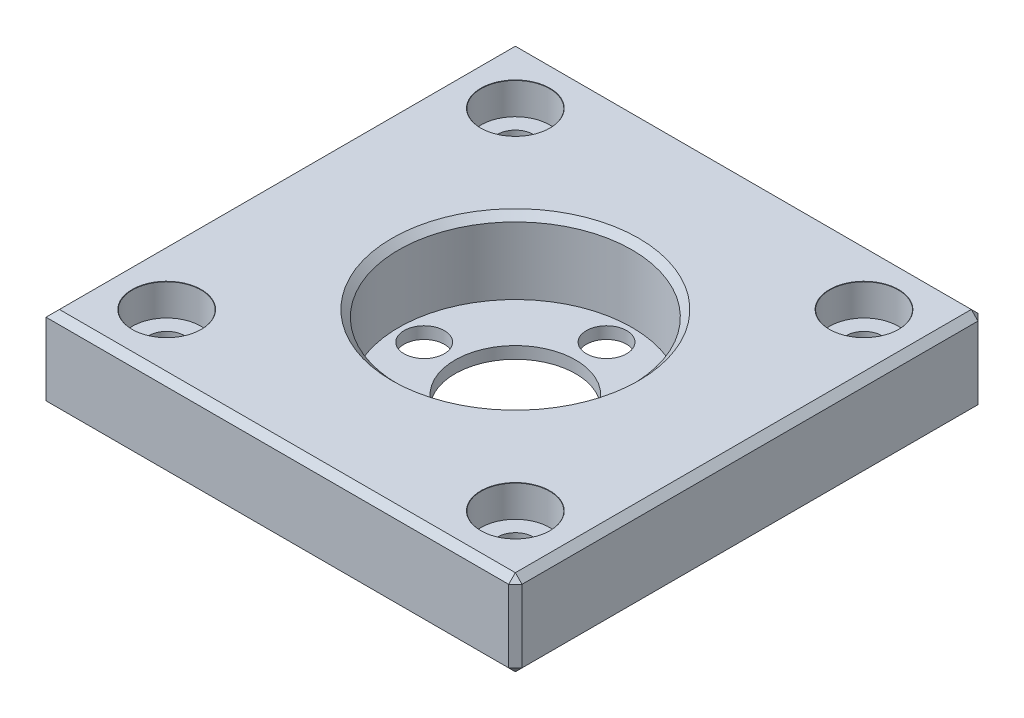
SolidWorks part; units mm, degrees
ref_plane "Front Plane" through (0, 0, 0) normal (0, 0, 1) x (1, 0, 0)
ref_plane "Top Plane" through (0, 0, 0) normal (0, 1, 0) x (1, 0, 0)
ref_plane "Right Plane" through (0, 0, 0) normal (1, 0, 0) x (0, 0, -1)
sketch "Sketch1" plane through (0, 0, 0) normal (0, 1, 0) x (1, 0, 0)
  line L1 (0, 0) -> (44.45, 0)
  line L2 (0, 0) -> (0, 44.45)
  line L3 (0, 44.45) -> (44.45, 44.45)
  line L4 (44.45, 0) -> (44.45, 44.45)
  dimension "D1" = 44.45
extrude "Boss-Extrude1" add sketch "Sketch1" along normal blind 8.128
sketch "Sketch2" plane through (0, 8.128, 0) normal (0, 1, 0) x (1, 0, 0)
  line L0 (22.225, 44.45) -> (22.225, 0) construction
  line L1 (44.45, 44.45) -> (0, 44.45) construction
  line L2 (0, 0) -> (44.45, 0) construction
  circle A0 centre (22.225, 22.225) radius 11.05
  point P4 (22.225, 26.2344)
  dimension "D1" = 22.1
extrude "Cut-Extrude1" cut sketch "Sketch2" against normal blind 7
sketch "Sketch3" plane through (0, 1.128, 0) normal (0, 1, 0) x (1, 0, 0)
  line L0 (22.225, 22.225) -> (22.225, 33.275) construction
  circle A0 centre (22.225, 30.861) radius 1.905
  circle A2 centre (22.225, 22.225) radius 11.05 construction
  circle A3 centre (30.861, 22.225) radius 1.905
  circle A4 centre (22.225, 13.589) radius 1.905
  circle A5 centre (13.589, 22.225) radius 1.905
  circle A6 centre (22.225, 22.225) radius 5.715
  point P5 (22.225, 22.225)
  point P16 (22.225, 22.225)
  dimension "D1" = 3.81
  dimension "D2" = 8.636
  dimension "D4" = 11.43
  dimension "D3" = 4
extrude "Cut-Extrude2" cut sketch "Sketch3" against normal through all
sketch "Sketch4" plane through (0, 8.128, 0) normal (0, 1, 0) x (1, 0, 0)
  line L0 (44.45, 44.45) -> (0, 44.45) construction
  line L1 (0, 44.45) -> (44.45, 44.45)
  line L2 (0, 44.45) -> (0, 0)
  line L3 (0, 0) -> (44.45, 0)
  line L4 (44.45, 44.45) -> (44.45, 0)
  line L5 (0, 44.45) -> (0, 0) construction
  line L6 (22.225, 44.45) -> (22.225, 0) construction
  line L7 (38.735, 5.715) -> (5.715, 5.715)
  line L8 (38.735, 5.715) -> (38.735, 38.735)
  line L9 (38.735, 38.735) -> (5.715, 38.735)
  line L10 (5.715, 5.715) -> (5.715, 38.735)
  line L11 (38.735, 5.715) -> (5.715, 38.735) construction
  line L12 (38.735, 38.735) -> (5.715, 5.715) construction
  point P9 (22.225, 22.225)
  point P14 (22.5364, 22.4087)
  point P15 (22.225, 22.225)
  dimension "D1" = 33.02
  dimension "D2" = 33.02
hole_wizard "CBORE for M3 SHCS1" positions "Sketch7" profile "Sketch8" counterbore size "M3" standard "ANSI Metric" end condition through all
sketch "Sketch7" plane through (0, 8.128, 0) normal (0, 1, 0) x (1, 0, 0)
  point P0 (5.715, 38.735)
  point P3 (38.735, 38.735)
  point P6 (38.735, 5.715)
  point P9 (5.715, 5.715)
sketch "Sketch8" plane through (5.715, 8.128, -38.735) normal (1, 0, 0) x (0, 0, 1)
  line L0 (0, 0) -> (0, 8.128)
  line L1 (0, 8.128) -> (1.7, 8.128)
  line L3 (1.7, 8.128) -> (1.7, 3)
  line L4 (3.25, 3) -> (1.7, 3)
  line L5 (3.25, 3) -> (3.25, 0.025)
  line L6 (3.25, 0.025) -> (3.275, 0)
  line L7 (3.275, 0) -> (0, 0)
  line L8 (-3.25, 0.025) -> (-3.275, 0) construction
  line L11 (0, -6.35) -> (0, 107.95) construction
  dimension "Thru Hole Dia." = 3.4
  dimension "Thru Hole Depth" = 8.128
  dimension "C'Bore Dia." = 6.5
  dimension "C'Bore Depth" = 3
  dimension "Near C'Sink Dia." = 6.55
  dimension "Near C'Sink Angle" = 90
chamfer "Chamfer1" distance 0.635 angle 45 10 edges at (44.45, 4.064, 0) (44.45, 8.128, -22.225) (22.225, 8.128, 0) (0, 8.128, -22.225) (22.225, 8.128, -44.45) (44.45, 4.064, -44.45) (44.45, 0, -22.225) (22.225, 0, -44.45) (0, 0, -22.225) (22.225, 0, 0)
chamfer "Chamfer2" distance 0.635 angle 45 1 edges at (22.225, 8.128, -11.175)
